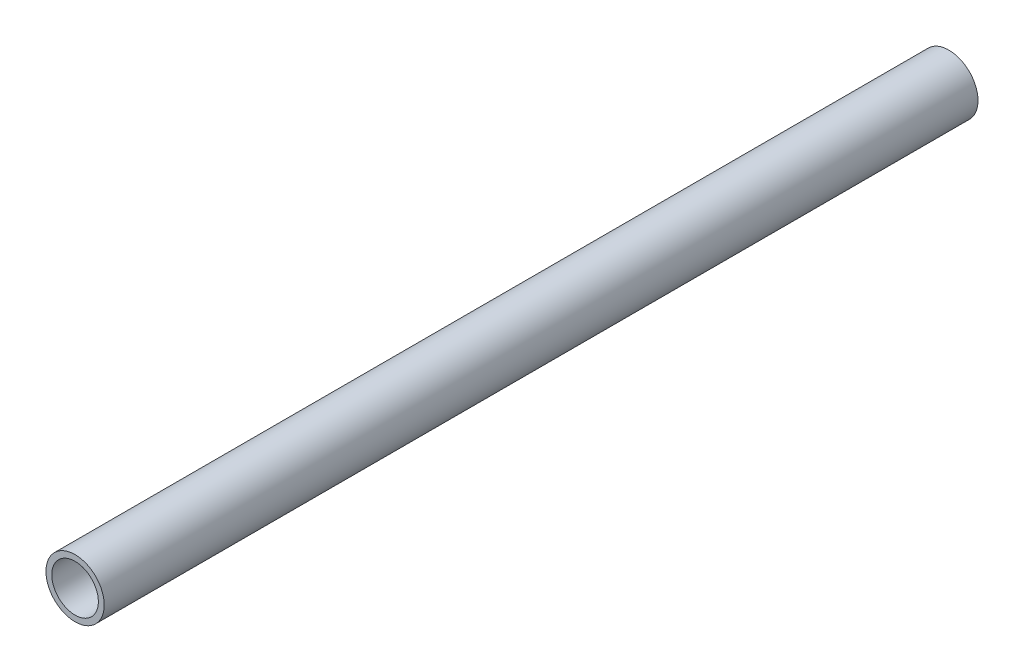
SolidWorks part; units mm, degrees
material "6063-O, Extruded Rod (SS)"
ref_plane "Płaszczyzna przednia" through (0, 0, 0) normal (0, 0, 1) x (1, 0, 0)
ref_plane "Płaszczyzna górna" through (0, 0, 0) normal (0, 1, 0) x (1, 0, 0)
ref_plane "Płaszczyzna prawa" through (0, 0, 0) normal (1, 0, 0) x (0, 0, -1)
sketch "Sketch1" plane through (0, 0, 0) normal (0, 0, 1) x (1, 0, 0)
  circle A0 centre (0, 0) radius 10
  circle A1 centre (0, 0) radius 8
  dimension "D1" = 20
  dimension "D2" = 2
extrude "Boss-Extrude1" add sketch "Sketch1" along normal blind 300
